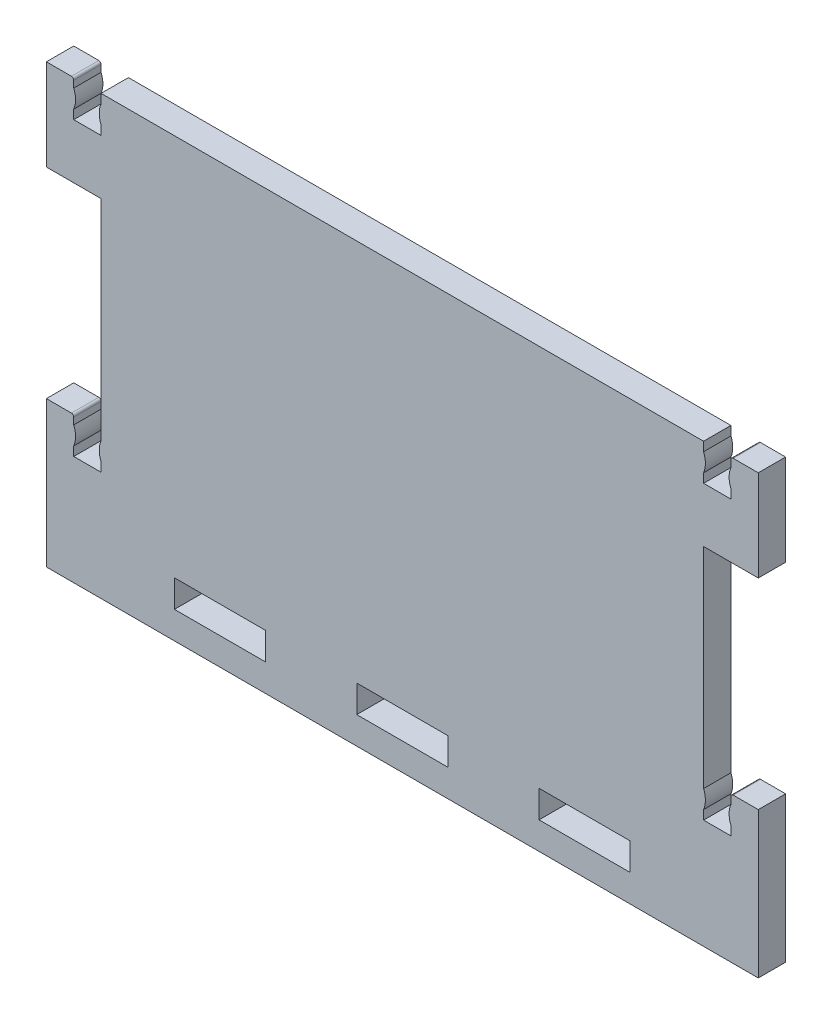
SolidWorks part; units mm, degrees
ref_plane "Front Plane" through (0, 0, 0) normal (0, 0, 1) x (1, 0, 0)
ref_plane "Top Plane" through (0, 0, 0) normal (0, 1, 0) x (1, 0, 0)
ref_plane "Right Plane" through (0, 0, 0) normal (1, 0, 0) x (0, 0, -1)
sketch "Sketch1" plane through (0, 0, 0) normal (0, 0, 1) x (1, 0, 0)
  line L0 (31.8434, -26.2183) -> (37.8434, -26.2183)
  line L1 (-34.2566, 21.7817) -> (31.8434, 21.7817)
  line L2 (-34.2566, 21.7817) -> (-34.2566, 20.7817)
  line L3 (-34.2566, -26.2183) -> (31.8434, -26.2183)
  line L4 (31.8434, 21.7817) -> (31.8434, 20.7817)
  line L5 (37.8434, -26.2183) -> (37.8434, -10.2183)
  line L6 (37.8434, -10.2183) -> (34.8434, -10.2183)
  line L7 (34.8434, -10.2183) -> (34.8434, -11.2183)
  line L8 (34.8434, -14.2183) -> (31.8434, -14.2183)
  line L9 (31.8434, 11.7817) -> (37.8434, 11.7817)
  line L10 (37.8434, 11.7817) -> (37.8434, 21.7817)
  line L11 (37.8434, 21.7817) -> (34.8434, 21.7817)
  line L12 (34.8434, 21.7817) -> (34.8434, 20.7817)
  line L13 (34.8434, 17.7817) -> (31.8434, 17.7817)
  line L14 (-1.2066, 21.7817) -> (-1.2066, -38.5562) construction
  line L15 (-6.2066, -20.2183) -> (3.7934, -20.2183)
  line L16 (-37.2566, 18.7817) -> (-37.2566, 17.7817)
  line L17 (-34.2566, 18.7817) -> (-34.2566, -11.2183)
  line L18 (-37.2566, -13.2183) -> (-37.2566, -14.2183)
  line L19 (33.3434, -14.2183) -> (33.3434, -10.2183) construction
  line L20 (23.7934, -20.2183) -> (13.7934, -20.2183)
  line L21 (23.7934, -20.2183) -> (23.7934, -23.2183)
  line L22 (23.7934, -23.2183) -> (13.7934, -23.2183)
  line L23 (13.7934, -20.2183) -> (13.7934, -23.2183)
  line L24 (3.7934, -20.2183) -> (3.7934, -23.2183)
  line L25 (3.7934, -23.2183) -> (-6.2066, -23.2183)
  line L26 (-37.2566, 21.7817) -> (-37.2566, 20.7817)
  line L27 (-34.2566, -13.2183) -> (-34.2566, -26.2183)
  line L28 (33.3434, 17.7817) -> (33.3434, 22.2785) construction
  line L29 (31.8434, -13.2183) -> (31.8434, -26.2183)
  line L30 (34.8434, -13.2183) -> (34.8434, -14.2183)
  line L31 (-6.2066, -20.2183) -> (-6.2066, -23.2183)
  line L32 (-16.2066, -20.2183) -> (-16.2066, -23.2183)
  line L33 (-26.2066, -23.2183) -> (-16.2066, -23.2183)
  line L34 (-26.2066, -20.2183) -> (-26.2066, -23.2183)
  line L35 (-26.2066, -20.2183) -> (-16.2066, -20.2183)
  line L36 (-37.2566, 17.7817) -> (-34.2566, 17.7817)
  line L37 (-40.2566, 21.7817) -> (-37.2566, 21.7817)
  line L38 (-40.2566, 11.7817) -> (-40.2566, 21.7817)
  line L39 (-34.2566, 11.7817) -> (-40.2566, 11.7817)
  line L40 (-37.2566, -14.2183) -> (-34.2566, -14.2183)
  line L41 (-37.2566, -10.2183) -> (-37.2566, -11.2183)
  line L42 (-40.2566, -10.2183) -> (-37.2566, -10.2183)
  line L43 (-40.2566, -26.2183) -> (-40.2566, -10.2183)
  line L44 (-34.2566, -26.2183) -> (-40.2566, -26.2183)
  line L45 (31.8434, 18.7817) -> (31.8434, -11.2183)
  line L46 (34.8434, 18.7817) -> (34.8434, 17.7817)
  arc A0 (34.8434, -13.2183) -> (34.8434, -11.2183) centre (37.2434, -12.2183) cw
  arc A1 (31.8434, -13.2183) -> (31.8434, -11.2183) centre (29.4434, -12.2183) ccw
  arc A2 (-37.2566, -13.2183) -> (-37.2566, -11.2183) centre (-39.6566, -12.2183) ccw
  arc A3 (-34.2566, -13.2183) -> (-34.2566, -11.2183) centre (-31.8566, -12.2183) cw
  arc A4 (34.8434, 20.7817) -> (34.8434, 18.7817) centre (37.2434, 19.7817) ccw
  arc A5 (31.8434, 20.7817) -> (31.8434, 18.7817) centre (29.4434, 19.7817) cw
  arc A6 (-34.2566, 20.7817) -> (-34.2566, 18.7817) centre (-31.8566, 19.7817) ccw
  arc A7 (-37.2566, 20.7817) -> (-37.2566, 18.7817) centre (-39.6566, 19.7817) cw
  point P36 (-1.2066, -23.2183)
  point P41 (-1.2066, -20.2183)
  dimension "D1" = 66.1
  dimension "D2" = 48
  dimension "D3" = 10
  dimension "D4" = 0
  dimension "D5" = 3
  dimension "D6" = 3
  dimension "D7" = 16
  dimension "D8" = 3
  dimension "D9" = 3
  dimension "D10" = 4
  dimension "D15" = 10
  dimension "D16" = 3
  dimension "D17" = 3
  dimension "D18" = 8.05
  dimension "D19" = 3
  dimension "D20" = 5
  dimension "D21" = 10
  dimension "D22" = 3
  dimension "D23" = 4
extrude "Boss-Extrude1" add sketch "Sketch1" along normal blind 3
fillet "Fillet1" radius 0.25 4 edges at (-37.2566, -10.2183, 1.5) (-37.2566, 21.7817, 1.5) (34.8434, 21.7817, 1.5) (34.8434, -10.2183, 1.5)
